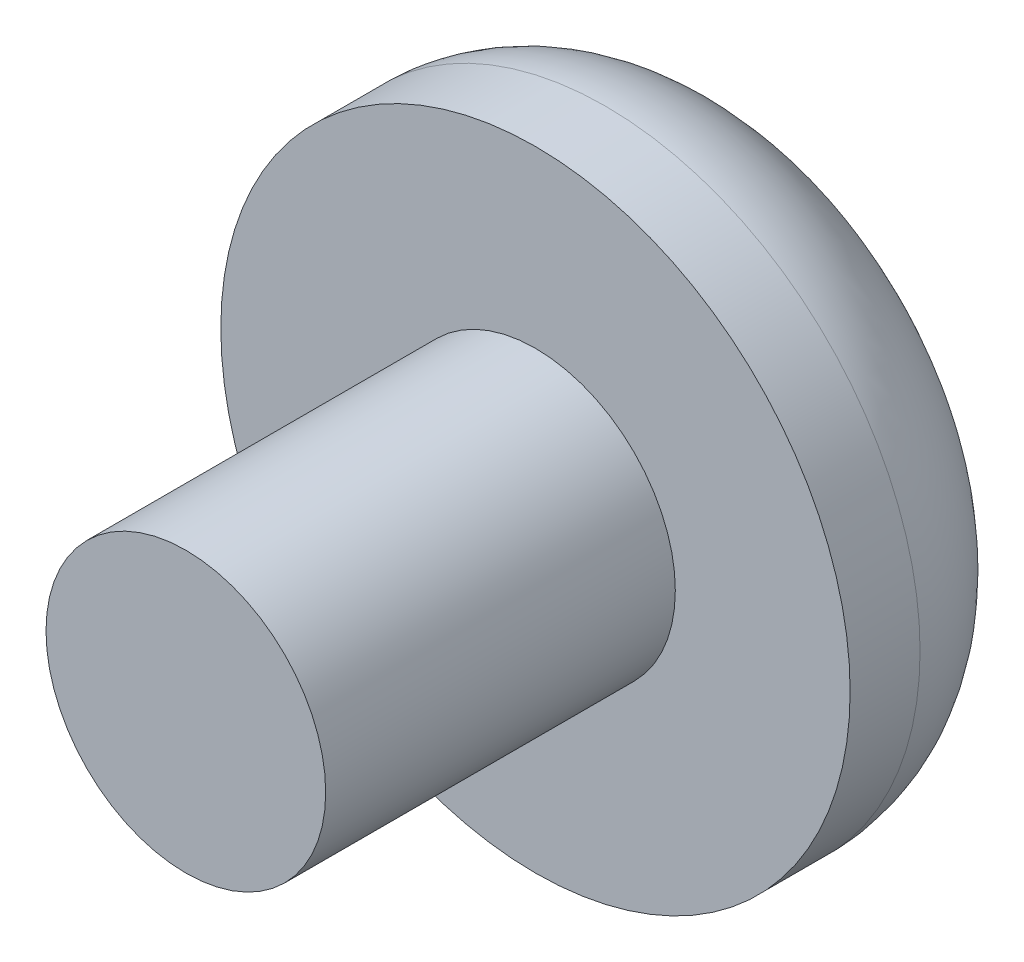
SolidWorks part; units mm, degrees
ref_plane "Plan de face" through (0, 0, 0) normal (0, 0, 1) x (1, 0, 0)
ref_plane "Plan de dessus" through (0, 0, 0) normal (0, 1, 0) x (1, 0, 0)
ref_plane "Plan de droite" through (0, 0, 0) normal (1, 0, 0) x (0, 0, -1)
sketch "Esquisse1" plane through (0, 0, 0) normal (0, 0, 1) x (1, 0, 0)
  circle A0 centre (0, 0) radius 2
  dimension "D1" = 4
extrude "Boss.-Extru.1" add sketch "Esquisse1" along normal blind 5
cosmetic thread "Représentation de filetage1" parameters "D2"=3.22
sketch "Esquisse2" plane through (0, 0, 0) normal (0, 0, 1) x (1, 0, 0)
  line L1 (-1.7187, 0.1158) -> (1.7187, 0.1158)
  line L2 (-1.7187, 0.1158) -> (-1.7187, -0.1158)
  line L3 (-1.7187, -0.1158) -> (1.7187, -0.1158)
  line L4 (1.7187, 0.1158) -> (1.7187, -0.1158)
  line L5 (-1.7187, 0.1158) -> (1.7187, -0.1158) construction
  line L6 (-1.7187, -0.1158) -> (1.7187, 0.1158) construction
  line L7 (-0.1158, -1.7187) -> (0.1158, -1.7187)
  line L8 (-0.1158, -1.7187) -> (-0.1158, 1.7187)
  line L9 (-0.1158, 1.7187) -> (0.1158, 1.7187)
  line L10 (0.1158, -1.7187) -> (0.1158, 1.7187)
  line L11 (-0.1158, -1.7187) -> (0.1158, 1.7187) construction
  line L12 (-0.1158, 1.7187) -> (0.1158, -1.7187) construction
  circle A0 centre (0, 0) radius 4.5
  dimension "D1" = 9
extrude "Boss.-Extru.2" add sketch "Esquisse2" against normal blind 3 contours A0 L10 L7 L8 L3 L2 L1 L9 L4
fillet "Congé1" radius 2 1 edges at (4.5, 0, -3)
